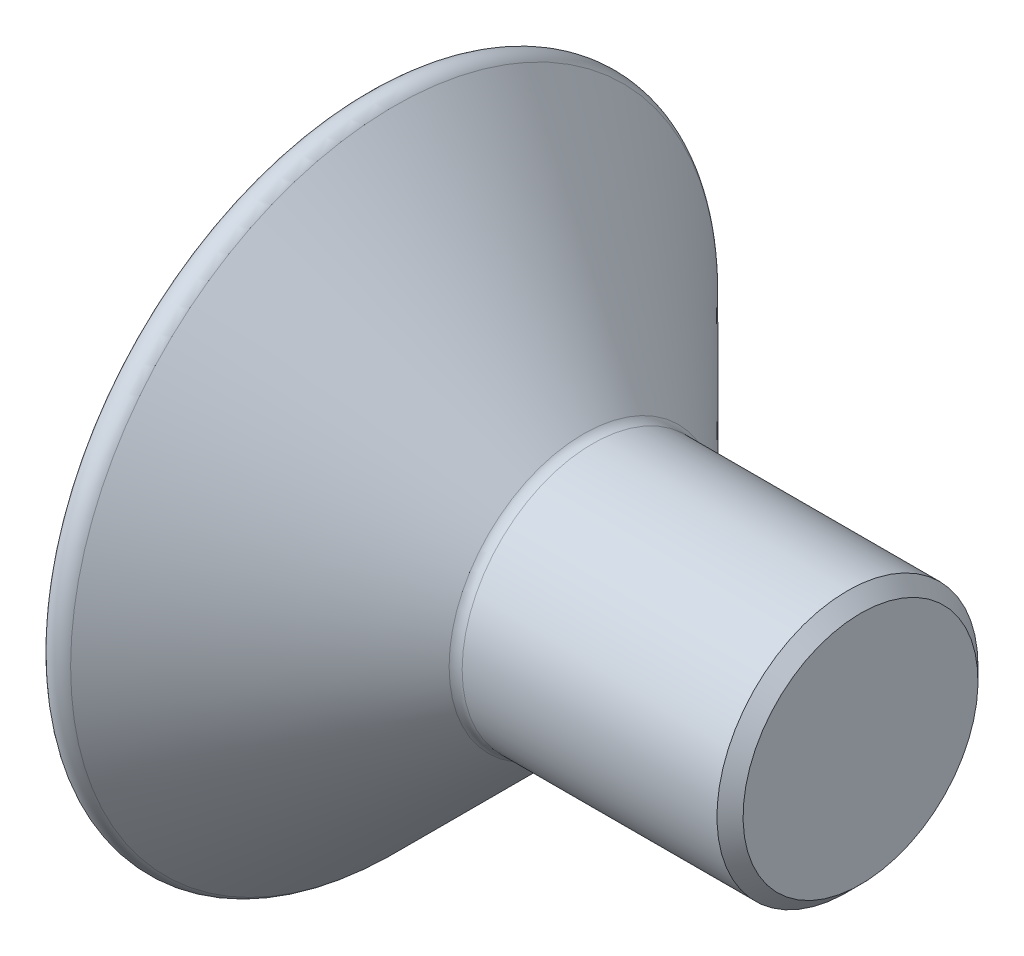
SolidWorks part; units mm, degrees
material "1060 合金"
ref_plane "Front" through (0, 0, 0) normal (0, 0, 1) x (1, 0, 0)
ref_plane "Top" through (0, 0, 0) normal (0, 1, 0) x (1, 0, 0)
ref_plane "Right" through (0, 0, 0) normal (1, 0, 0) x (0, 0, -1)
sketch "Sketch1" plane through (0, 0, 0) normal (0, 0, 1) x (1, 0, 0)
  line L0 (0, 0) -> (0, 3.36)
  line L1 (0, 3.36) -> (1.86, 1.5)
  line L2 (1.86, 1.5) -> (8, 1.5)
  line L3 (8, 1.5) -> (8, 0)
  line L4 (8, 0) -> (0, 0)
  line L5 (-0.5871, 0) -> (5.4927, 0) construction
  dimension "l" = 8
  dimension "k" = 1.86
  dimension "d" = 3
  dimension "D1" = 45
revolve "Base" add sketch "Sketch1" angle 360 about L5
cosmetic thread "ThreadCosmetic1" [suppressed] parameters "b"=6, "D2"=2.459
cosmetic thread "装饰螺纹线1" parameters "D2"=2.459
sketch "Sketch2" plane through (0, 0, 0) normal (1, 0, 0) x (0, 0, -1)
  line L1 (1.1547, 0) -> (0.5774, 1)
  line L2 (0.5774, 1) -> (-0.5774, 1)
  line L3 (-0.5774, 1) -> (-1.1547, 0)
  line L4 (-1.1547, 0) -> (-0.5774, -1)
  line L5 (-0.5774, -1) -> (0.5774, -1)
  line L6 (0.5774, -1) -> (1.1547, 0)
  circle A0 centre (0, 0) radius 1 construction
  dimension "s" = 2
extrude "HexagonSocket" cut sketch "Sketch2" along normal blind 1.1
sketch "Sketch3" plane through (0, 0, 0) normal (0, 0, 1) x (1, 0, 0)
  line L0 (-0.4391, 0) -> (4.425, 0) construction
  line L1 (1.1, 0) -> (1.1, -1) construction
  line L2 (1.1, 1) -> (1.6774, 0)
  line L3 (1.6774, 0) -> (1.1, -1) construction
  line L4 (1.1, 1) -> (1.1, 0)
  line L5 (1.1, 0) -> (1.6774, 0)
  line L7 (1.1, 1) -> (1.1, 0) construction
  dimension "D1" = 120
revolve "Cut-Revolve1" cut sketch "Sketch3" angle 360 about L0
chamfer "Chamfer" distance 0.2705 angle 45 1 edges at (8, 0, 1.5)
sketch "Sketch4" plane through (0, 0, 0) normal (0, 1, 0) x (1, 0, 0)
  line L0 (11.8531, 0) -> (-2.694, 0) construction
  line L1 (-2, 7.77) -> (3, 7.77)
  line L2 (-2, 7.77) -> (-2, 2.77)
  line L3 (-2, 2.77) -> (3, 2.77)
  line L4 (3, 7.77) -> (3, 2.77)
  line L5 (0, 3.36) -> (0, -3.36) construction
  dimension "dk" = 5.54
  dimension "D2" = 2
  dimension "D3" = 5
  dimension "D4" = 5
sketch "Sketch5" plane through (0, 0, 0) normal (0, 0, 1) x (1, 0, 0)
  line L0 (7.7295, 1.2657) -> (7.8648, 1.5)
  line L1 (7.8648, 1.5) -> (7.8648, 1.7705)
  line L2 (7.8648, 1.7705) -> (7.5943, 1.7705)
  line L3 (7.5943, 1.7705) -> (7.5943, 1.5)
  line L4 (7.5943, 1.5) -> (7.7295, 1.2657)
  line L5 (0, 0) -> (10.6885, 0) construction
  line L6 (7.7295, 1.5) -> (7.7295, -1.5) construction
  dimension "D1" = 3
  dimension "D2" = 0.2705
revolve "Cut-Revolve10" [suppressed] cut sketch "Sketch5" angle 360 about L5
pattern_linear "LPattern10" [suppressed] count 18 spacing 0.3246 along (1, 0, 0)
ref_plane "基准面2" through (0, 0, 0) normal (0, 0.5, 0.866) x (1, 0, 0)
sketch "草图1" plane through (0, 0, 0) normal (-1, 0, 0) x (0, 0, 1)
  circle A0 centre (0, 0) radius 3.36
  circle M1 centre (0, 0) radius 3.36
  line M2 (-0.5774, -1) -> (-1.1547, 0)
  line M3 (-1.1547, 0) -> (-0.5774, 1)
  line M4 (-0.5774, 1) -> (0.5774, 1)
  line M5 (0.5774, 1) -> (1.1547, 0)
  line M6 (1.1547, 0) -> (0.5774, -1)
  line M7 (0.5774, -1) -> (-0.5774, -1)
  dimension "D1" = 6.72
extrude "凸台-拉伸4" add sketch "草图1" against normal blind 0.5 contours M1 M7 M2 M3 M4 M5 M6
sketch "草图5" plane through (0, 0, 0) normal (0, 0.5, 0.866) x (1, 0, 0)
  line L0 (2.633, -0.6458) -> (0.5, -2.7787)
  line L1 (0.5, -2.7787) -> (0.5, -3.36)
  line L2 (0.5, -3.36) -> (2.633, -1.227)
  line L3 (2.633, -1.227) -> (2.633, -0.6458)
  line L5 (0.5, -3.36) -> (0.5, 3.36) construction
  line L6 (0, -3.36) -> (0.5, -3.36) construction
  line L7 (7.7295, 0) -> (1.86, 0) construction
  dimension "D1" = 45
  dimension "D2" = 0
  dimension "D3" = 0.5813
  dimension "D4" = 0.6458
revolve "旋转7" add sketch "草图5" angle 360 about axis through (1.86, 0, 0) along (-1, 0, 0)
ref_plane "基准面4" through (2.36, 0, 0) normal (1, 0, 0) x (0, 0, -1)
sketch "草图6" plane through (2.36, 0, 0) normal (1, 0, 0) x (0, 0, -1)
  circle A0 centre (0, 0) radius 1.5
  dimension "D1" = 3
sketch "草图8" plane through (0, 0, 0) normal (-1, 0, 0) x (0, 0, 1)
  circle A1 centre (0, 0) radius 3.36
  circle A2 centre (0, 0) radius 3.36
  circle M2 centre (0, 0) radius 3.36
  line M3 (-0.5774, -1) -> (-1.1547, 0)
  line M4 (-1.1547, 0) -> (-0.5774, 1)
  line M5 (-0.5774, 1) -> (0.5774, 1)
  line M6 (0.5774, 1) -> (1.1547, 0)
  line M7 (1.1547, 0) -> (0.5774, -1)
  line M8 (0.5774, -1) -> (-0.5774, -1)
  dimension "D1" = 0
extrude "凸台-拉伸6" add sketch "草图8" along normal blind 0.15 contours M2 M8 M3 M4 M5 M6 M7
sketch "草图11" plane through (0, 0, 0) normal (0, 0.5, 0.866) x (1, 0, 0)
  line L0 (0.5, -3.36) -> (0.2174, -3.6426)
  line L3 (-0.15, -3.36) -> (0.5, -3.36) construction
  line L4 (-0.15, -3.36) -> (0.5, -3.36)
  line L5 (0.2174, -3.6426) -> (0, -3.86)
  line L6 (0, -3.86) -> (-0.15, -3.71)
  line L7 (-0.15, -3.71) -> (-0.15, -3.36)
  dimension "D1" = 45
  dimension "D2" = 0.3075
  dimension "D3" = 0.2121
  dimension "D4" = 0.35
  dimension "D5" = 90
  dimension "D6" = 45
revolve "旋转8" add sketch "草图11" angle 360
fillet "圆角5" radius 0.2 1 edges at (0, 0, -3.86)
extrude "切除-拉伸1" cut sketch "草图6" along normal through all from offset 3.14 contours A0
fillet "圆角6" radius 0.15 1 edges at (2.36, 0, 1.5)
chamfer "倒角1" distance 0.15 angle 45 1 edges at (5.5, 1.5, 0)
equation "\"D1@Chamfer\" = (  \"d@Sketch1\" - \"D2@ThreadCosmetic1\" )  / 2"
equation "\"D1@Sketch5\" = \"d@Sketch1\""
equation "\"D2@Sketch5\" =  ( \"d@Sketch1\" - \"D2@ThreadCosmetic1\" )  / 2"
equation "\"D3@LPattern10\" = \"D2@Sketch5\" * 1.2"
equation "\"D1@LPattern10\" = \"b@ThreadCosmetic1\" / \"D3@LPattern10\""
